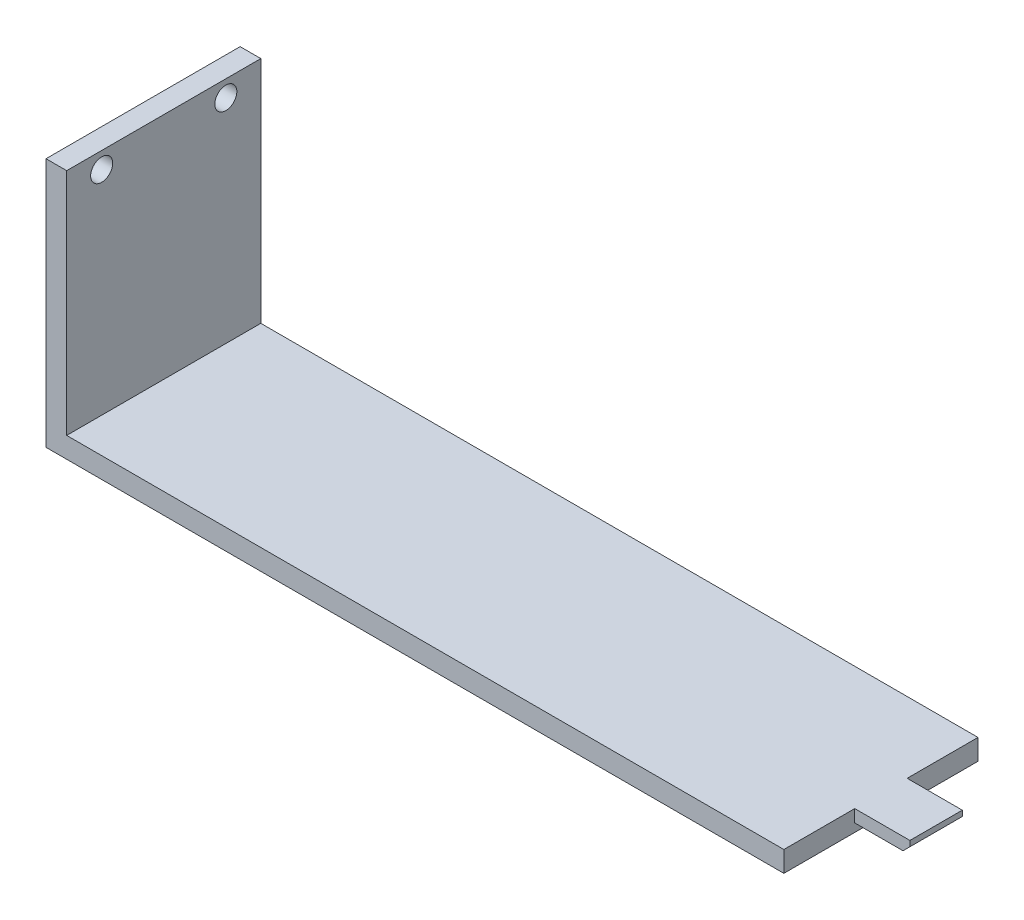
SolidWorks part; units mm, degrees
ref_plane "Front Plane" through (0, 0, 0) normal (0, 0, 1) x (1, 0, 0)
ref_plane "Top Plane" through (0, 0, 0) normal (0, 1, 0) x (1, 0, 0)
ref_plane "Right Plane" through (0, 0, 0) normal (1, 0, 0) x (0, 0, -1)
sketch "Sketch1" plane through (0, 0, 0) normal (0, 1, 0) x (1, 0, 0)
  line L1 (-49.6107, 11.3223) -> (57.3893, 11.3223)
  line L2 (-49.6107, 11.3223) -> (-49.6107, -16.8277)
  line L3 (-49.6107, -16.8277) -> (57.3893, -16.8277)
  line L4 (57.3893, 11.3223) -> (57.3893, -16.8277)
  dimension "D1" = 107
  dimension "D2" = 28.15
extrude "Boss-Extrude1" add sketch "Sketch1" along normal blind 3
sketch "Sketch2" plane through (57.3893, 0, 0) normal (1, 0, 0) x (0, 0, -1)
  line L0 (-16.8277, 3) -> (11.3223, 3) construction
  line L1 (-6.5527, 3) -> (1.0473, 3)
  line L2 (-6.5527, 3) -> (-6.5527, 1.2)
  line L3 (-6.5527, 1.2) -> (1.0473, 1.2)
  line L4 (1.0473, 3) -> (1.0473, 1.2)
  line L5 (-16.8277, 0) -> (11.3223, 0) construction
  point P8 (-2.7527, 0)
  dimension "D1" = 7.6
  dimension "D2" = 1.8
  dimension "D3" = 3.8
extrude "Boss-Extrude2" add sketch "Sketch2" along normal blind 8
chamfer "Chamfer1" distance 1 angle 45 1 edges at (65.3893, 1.2, 2.7527)
sketch "Sketch3" plane through (0, 3, 0) normal (0, 1, 0) x (1, 0, 0)
  line L0 (-49.6107, -16.8277) -> (57.3893, -16.8277) construction
  line L1 (-49.6107, 11.3223) -> (-46.6107, 11.3223)
  line L2 (-49.6107, 11.3223) -> (-49.6107, -16.8277)
  line L3 (-49.6107, -16.8277) -> (-46.6107, -16.8277)
  line L4 (-46.6107, 11.3223) -> (-46.6107, -16.8277)
  dimension "D1" = 3
extrude "Boss-Extrude3" add sketch "Sketch3" along normal blind 33.25
sketch "Sketch4" plane through (-49.6107, 0, 0) normal (-1, 0, 0) x (0, 0, 1)
  line L0 (-11.3223, 36.25) -> (16.8277, 36.25) construction
  circle A0 centre (-6.2473, 33.85) radius 1.6
  circle A1 centre (11.7527, 33.85) radius 1.6
  point P6 (2.7527, 36.25)
  dimension "D1" = 2.4
  dimension "D2" = 2.4
  dimension "D3" = 3.2
  dimension "D4" = 3.2
  dimension "D5" = 18
  dimension "D6" = 9
extrude "Cut-Extrude1" cut sketch "Sketch4" against normal blind 33.25
